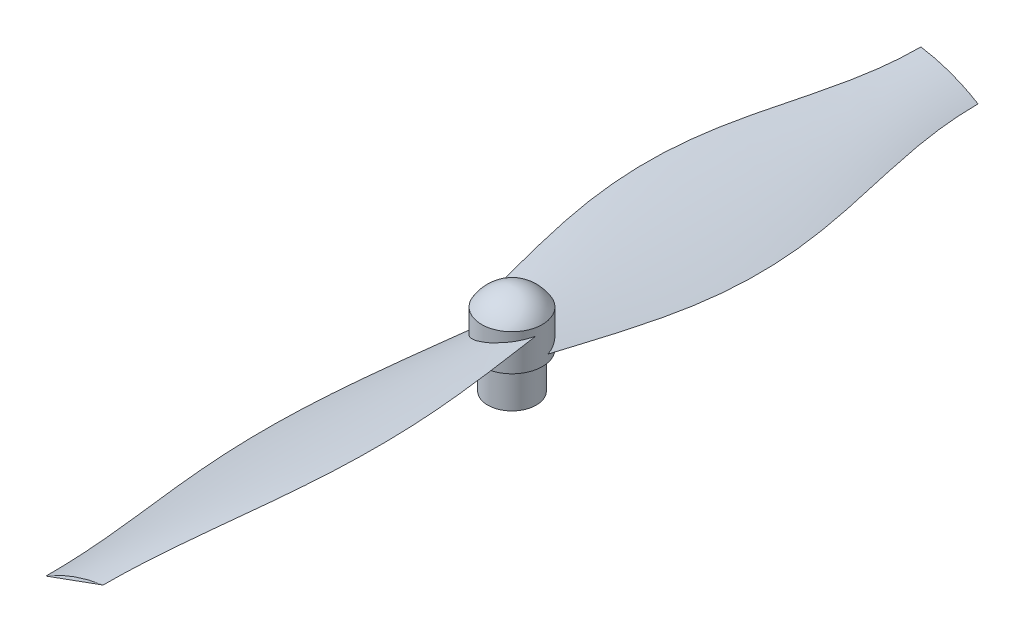
SolidWorks part; units mm, degrees
ref_plane "Front Plane" through (0, 0, 0) normal (0, 0, 1) x (1, 0, 0)
ref_plane "Top Plane" through (0, 0, 0) normal (0, 1, 0) x (1, 0, 0)
ref_plane "Right Plane" through (0, 0, 0) normal (1, 0, 0) x (0, 0, -1)
sketch "Sketch1" plane through (0, 0, 0) normal (0, 0, 1) x (1, 0, 0)
  line L0 (0, 0) -> (0, 15)
  line L1 (0, 0) -> (4, 0)
  line L2 (4, 0) -> (4, 6)
  line L3 (4, 6) -> (5, 6)
  line L4 (5, 6) -> (5, 12)
  arc A0 (0, 15) -> (5, 12) centre (-0.198, 9.0033) cw
  dimension "D6" = 6
  dimension "D1" = 15
  dimension "D2" = 4
  dimension "D3" = 6
  dimension "D4" = 1
  dimension "D5" = 6
revolve "Revolve1" add sketch "Sketch1" angle 360 about L0
sketch "Sketch2" plane through (0, 0, 0) normal (0, -1, 0) x (1, 0, 0)
  line L1 (2.8868, 0) -> (1.4434, 2.5)
  line L2 (1.4434, 2.5) -> (-1.4434, 2.5)
  line L3 (-1.4434, 2.5) -> (-2.8868, 0)
  line L4 (-2.8868, 0) -> (-1.4434, -2.5)
  line L5 (-1.4434, -2.5) -> (1.4434, -2.5)
  line L6 (1.4434, -2.5) -> (2.8868, 0)
  circle A0 centre (0, 0) radius 2.5 construction
  dimension "D1" = 5
extrude "Cut-Extrude1" cut sketch "Sketch2" against normal blind 7
ref_plane "Plane1" through (0, 0, 20) normal (0, 0, 1) x (1, 0, 0)
ref_plane "Plane2" through (0, 0, 72) normal (0, 0, 1) x (1, 0, 0)
ref_plane "Plane3" through (0, 0, -20) normal (0, 0, -1) x (-1, 0, 0)
ref_plane "Plane4" through (0, 0, -72) normal (0, 0, 1) x (1, 0, 0)
sketch "Sketch3" plane through (0, 0, 0) normal (0, 0, 1) x (1, 0, 0)
  line L0 (0, 0) -> (0, 17.2286) construction
  line L1 (4.6985, 10.7101) -> (-4.6985, 7.2899)
  line L2 (-4, 0) -> (4, 0) construction
  arc A0 (-4.6985, 7.2899) -> (4.6985, 10.7101) centre (8.3777, -14.0177) cw
  point P6 (0, 9)
  dimension "D5" = 25
  dimension "D1" = 10
  dimension "D2" = 70
  dimension "D3" = 70
  dimension "D4" = 9
sketch "Sketch4" plane through (0, 0, 20) normal (0, 0, 1) x (1, 0, 0)
  line L0 (0, 0) -> (0, 21.3924) construction
  line L1 (-8.4572, 5.9218) -> (8.4572, 12.0782)
  line L2 (-4, 0) -> (4, 0) construction
  arc A0 (-8.4572, 5.9218) -> (8.4572, 12.0782) centre (27.1879, -65.6982) cw
  point P7 (0, 9)
  dimension "D4" = 80
  dimension "D5" = 80
  dimension "D1" = 18
  dimension "D2" = 70
  dimension "D3" = 9
sketch "Sketch5" plane through (0, 0, 72) normal (0, 0, 1) x (1, 0, 0)
  line L0 (0, 0) -> (0, 22.1252) construction
  line L1 (-4.6985, 7.2899) -> (4.6985, 10.7101)
  line L2 (-4, 0) -> (4, 0) construction
  arc A0 (-4.6985, 7.2899) -> (4.6985, 10.7101) centre (8.3777, -14.0177) cw
  point P7 (0, 9)
  dimension "D4" = 25
  dimension "D1" = 10
  dimension "D2" = 70
  dimension "D3" = 9
surface "Surface-Loft2"
sketch "Sketch7" plane through (0, 0, 0) normal (0, 0, 1) x (1, 0, 0)
  line L0 (0, 0) -> (0, 18) construction
  line L1 (4.6985, 7.2899) -> (-4.6985, 10.7101)
  line L2 (-4, 0) -> (4, 0) construction
  arc A0 (4.6985, 7.2899) -> (-4.6985, 10.7101) centre (-8.3777, -14.0177) ccw
  point P6 (-3.9486, 11.1578)
  point P7 (0, 9)
  dimension "D4" = 25
  dimension "D1" = 10
  dimension "D2" = 70
  dimension "D3" = 9
sketch "Sketch8" plane through (0, 0, -20) normal (0, 0, -1) x (-1, 0, 0)
  line L0 (0, 0) -> (0, 19.7896) construction
  line L1 (-8.4572, 5.9218) -> (8.4572, 12.0782)
  line L3 (-4, 0) -> (4, 0) construction
  arc A0 (-8.4572, 5.9218) -> (8.4572, 12.0782) centre (27.1879, -65.6982) cw
  point P9 (0, 9)
  dimension "D4" = 80
  dimension "D1" = 18
  dimension "D2" = 70
  dimension "D3" = 9
sketch "Sketch10" plane through (0, 0, -72) normal (0, 0, 1) x (1, 0, 0)
  line L0 (0, 0) -> (0, 21.6335) construction
  line L1 (4.6985, 7.2899) -> (-4.6985, 10.7101)
  line L4 (-4, 0) -> (4, 0) construction
  arc A0 (4.6985, 7.2899) -> (-4.6985, 10.7101) centre (-8.3777, -14.0177) ccw
  point P9 (0, 9)
  point P11 (0, 9)
  dimension "D4" = 25
  dimension "D1" = 10
  dimension "D2" = 70
  dimension "D3" = 9
surface "Surface-Loft3"
